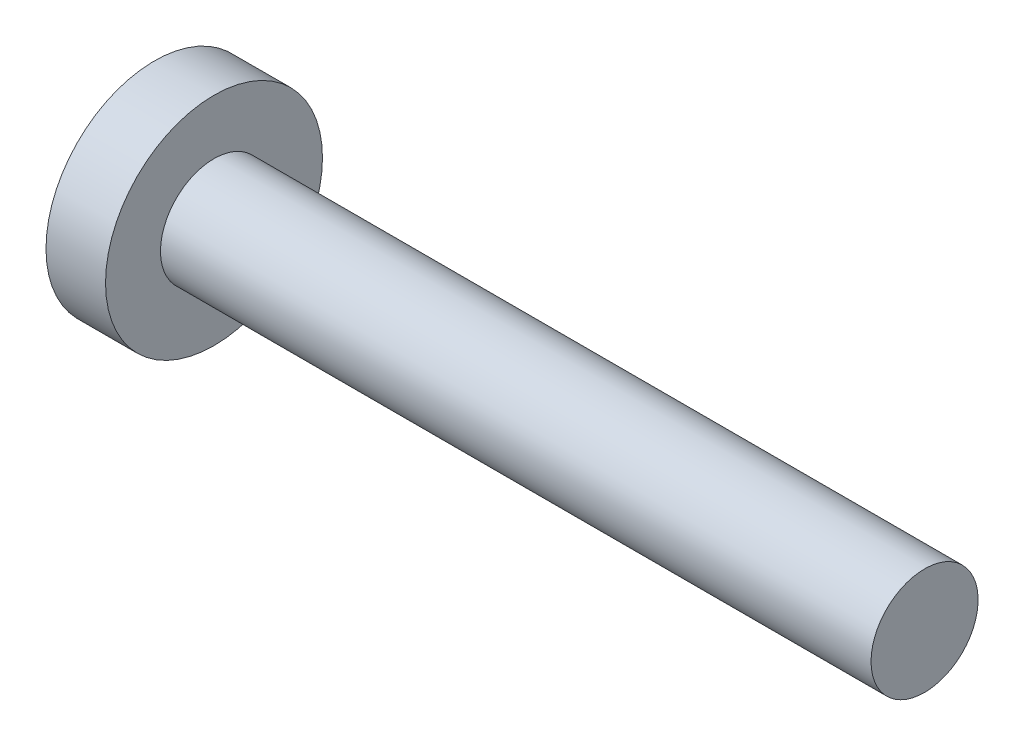
SolidWorks part; units mm, degrees
ref_plane "Plane1" through (0, 0, 0) normal (0, 0, 1) x (1, 0, 0)
ref_plane "Plane2" through (0, 0, 0) normal (0, 1, 0) x (1, 0, 0)
ref_plane "Plane3" through (0, 0, 0) normal (1, 0, 0) x (0, 0, -1)
sketch "BodySke" plane through (0, 0, 0) normal (0, 0, 1) x (1, 0, 0)
  line L0 (0, 0) -> (30.0169, 0)
  line L1 (30.0169, 0) -> (30.0169, 2)
  line L2 (30.0169, 2) -> (3.4708, 2)
  line L4 (-15.875, 0) -> (82.55, 0) construction
  line L8 (3.4708, 2) -> (3.4708, 4.0523)
  line L9 (3.4708, 4.0523) -> (1.2467, 4.0523)
  arc A0 (0, 0) -> (1.2467, 4.0523) centre (7.3998, -0.0586) cw
  arc A1 (0.0169, 0.4997) -> (0, 0) centre (7.4, 0) ccw construction
  dimension "D3" = 0.9994
  dimension "D4" = 0.0169
  dimension "Length" = 30
  dimension "Diameter" = 4
revolve "Base-Revolve" add sketch "BodySke" angle 360 about L4
cosmetic thread "ThreadCosmetic" [suppressed] parameters "Thread_length"=26.546, "Thread_minor"=1.8
sketch "Sketch2" plane through (0, 0, 0) normal (1, 0, 0) x (0, 0, -1)
  line L0 (3, -0.5) -> (-3, -0.5)
  line L1 (3, -0.5) -> (3, 0.5)
  line L2 (-3, 0.5) -> (3, 0.5)
  line L3 (-3, 0.5) -> (-3, -0.5)
  dimension "D1" = 6
  dimension "Slot_width" = 1
  dimension "D3" = 3
  dimension "D4" = 0.5
extrude "Slot" cut sketch "Sketch2" along normal blind 1.5
sketch "Sketch3" plane through (0, 0, 0) normal (1, 0, 0) x (0, 0, -1)
  line L0 (0.415, -1.72) -> (-0.415, -1.72)
  line L1 (0.415, -1.72) -> (0.415, 1.72)
  line L2 (-0.415, 1.72) -> (0.415, 1.72)
  line L3 (-0.415, 1.72) -> (-0.415, -1.72)
  dimension "D1" = 0.415
  dimension "Cross_width" = 0.83
  dimension "D2" = 1.72
  dimension "Cross_dia" = 3.44
ref_plane "Plane4" through (2.33, 0, 0) normal (1, 0, 0) x (0, 0, -1)
sketch "Sketch4" plane through (2.33, 0, 0) normal (1, 0, 0) x (0, 0, -1)
  line L0 (0.2075, -0.2075) -> (-0.2075, -0.2075)
  line L1 (0.2075, -0.2075) -> (0.2075, 0.2075)
  line L2 (-0.2075, 0.2075) -> (0.2075, 0.2075)
  line L3 (-0.2075, 0.2075) -> (-0.2075, -0.2075)
  dimension "D1" = 0.415
  dimension "D2" = 0.415
  dimension "D3" = 0.2075
  dimension "D4" = 0.2075
loft "Cross" cut profiles "Sketch3", "Sketch4"
pattern_circular "CirPattern1" count 2 every 90 about axis through (0, 0, 0) along (1, 0, 0) of "Cross"
